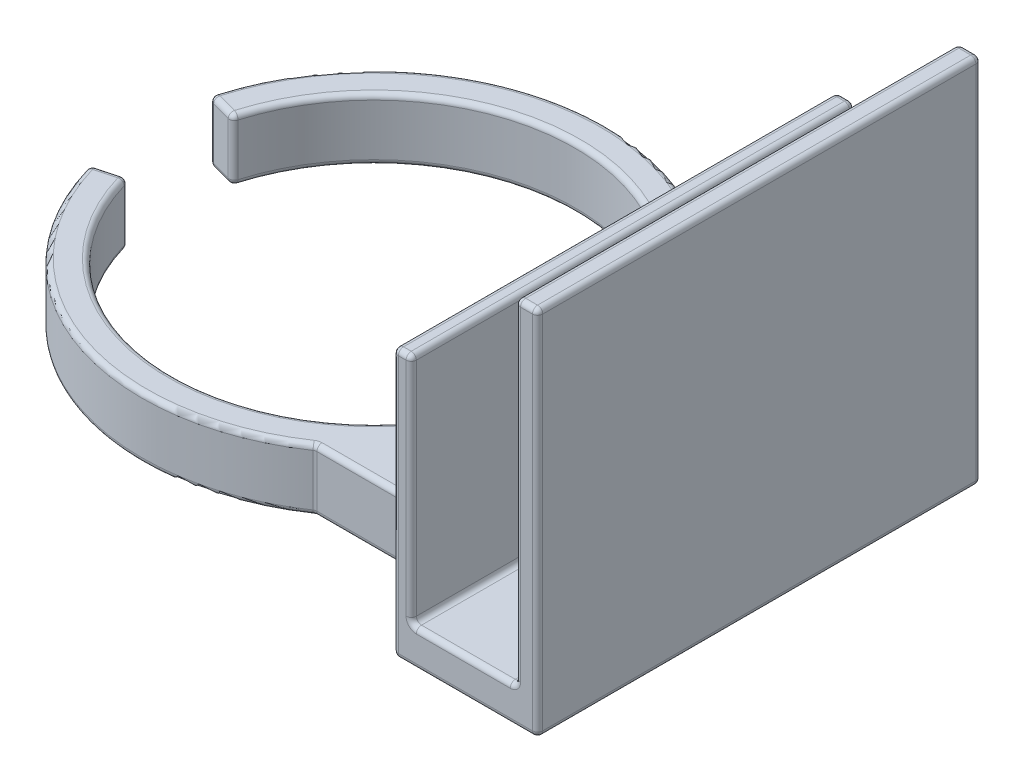
SolidWorks part; units mm, degrees
ref_plane "Front Plane" through (0, 0, 0) normal (0, 0, 1) x (1, 0, 0)
ref_plane "Top Plane" through (0, 0, 0) normal (0, 1, 0) x (1, 0, 0)
ref_plane "Right Plane" through (0, 0, 0) normal (1, 0, 0) x (0, 0, -1)
sketch "Sketch1" plane through (0, 0, 0) normal (0, 1, 0) x (1, 0, 0)
  line L1 (46.7214, 25) -> (46.7214, 5)
  line L2 (44.7214, 5) -> (46.7214, 5)
  line L3 (37.4166, 25) -> (46.7214, 25)
  line L5 (-45, 0) -> (74.7214, 0)
  line L6 (74.7214, 43) -> (74.7214, 0)
  line L7 (25.6125, 37) -> (46.7214, 37)
  line L12 (46.7214, 37) -> (46.7214, 43)
  line L13 (46.7214, 43) -> (74.7214, 43)
  arc A1 (37.4166, 25) -> (44.7214, 5) centre (0, 0) cw
  arc A4 (25.6125, 37) -> (-45, 0) centre (0, 0) ccw
  dimension "D1" = 5
  dimension "D7" = 45
  dimension "D5" = 45
  dimension "D2" = 2
  dimension "D3" = 12
  dimension "D4" = 28
  dimension "D6" = 20
  dimension "D8" = 43
extrude "Boss-Extrude1" add sketch "Sketch1" along normal blind 12
sketch "Sketch3" plane through (0, 12, 0) normal (0, 1, 0) x (1, 0, 0)
  line L2 (-43.4667, 11.6469) -> (-37.6711, 10.0939)
  line L3 (-45, 0) -> (39, 0)
  arc A1 (-45, 0) -> (-43.4667, 11.6469) centre (0, 0) cw
  arc A3 (39, 0) -> (-37.6711, 10.0939) centre (0, 0) ccw
  point P1 (0, 0)
  dimension "D1" = 39
  dimension "D2" = 45
extrude "Cut-Extrude2" cut sketch "Sketch3" against normal through all
ref_plane "Plane1" through (0, 0, 0) normal (0, 0, 1) x (1, 0, 0)
sketch "Sketch4" plane through (0, 12, 0) normal (0, 1, 0) x (1, 0, 0)
  line L0 (-55, 0) -> (55, 0) construction
  line L1 (46.7214, 43) -> (74.7214, 43)
  line L2 (46.7214, 43) -> (46.7214, 0)
  line L3 (46.7214, 0) -> (74.7214, 0)
  line L4 (74.7214, 43) -> (74.7214, 0)
  line L5 (74.7214, 0) -> (74.7214, 43) construction
extrude "Boss-Extrude2" add sketch "Sketch4" along normal blind 50
sketch "Sketch5" plane through (0, 0, 0) normal (0, -1, 0) x (1, 0, 0)
  line L0 (55, 0) -> (-55, 0) construction
  line L1 (74.7214, -43) -> (46.7214, -43)
  line L2 (74.7214, -43) -> (74.7214, 0)
  line L3 (74.7214, 0) -> (46.7214, 0)
  line L4 (46.7214, -43) -> (46.7214, 0)
  line L5 (46.7214, -5) -> (46.7214, -25) construction
extrude "Boss-Extrude3" add sketch "Sketch5" along normal blind 10
sketch "Sketch6" plane through (0, 62, 0) normal (0, 1, 0) x (1, 0, 0)
  line L0 (74.7214, 43) -> (46.7214, 43) construction
  line L1 (50.2117, 43) -> (70.4117, 43)
  line L2 (50.2117, 43) -> (50.2117, 0)
  line L3 (50.2117, 0) -> (70.4117, 0)
  line L4 (70.4117, 43) -> (70.4117, 0)
  line L5 (-55, 0) -> (55, 0) construction
  line L9 (46.7214, 43) -> (46.7214, 0) construction
  dimension "D1" = 20.2
  dimension "D3" = 3.4903
extrude "Cut-Extrude3" cut sketch "Sketch6" against normal blind 65
mirror "Mirror1" about plane through (0, 0, 0) normal (0, 0, 1) of "Boss-Extrude1", "Cut-Extrude2", "Boss-Extrude2", "Boss-Extrude3", "Cut-Extrude3"
sketch "Sketch7" plane through (46.7214, 0, 0) normal (-1, 0, 0) x (0, 0, 1)
  line L0 (43, 62) -> (43, -10) construction
  line L1 (-43, 62) -> (43, 62)
  line L2 (-43, 62) -> (-43, 42)
  line L3 (-43, 42) -> (43, 42)
  line L4 (43, 62) -> (43, 42)
  dimension "D1" = 20
extrude "Cut-Extrude4" cut sketch "Sketch7" against normal up to next
fillet "Fillet5" radius 1 72 edges at (46.7214, 42, 0) (48.4665, 42, -43) (48.4665, 42, 43) (50.2117, 42, 0) (60.3117, -3, 43) (50.2117, 19.5, 43) (70.4117, 29.5, 43) (46.7214, 0, 31) (60.7214, -10, 43) (46.7214, 12, 31) (72.5665, 62, 43) (-40.5689, 0, 10.8704) (-40.5689, 12, 10.8704) (-37.6711, 6, 10.0939) (42.2689, 0, 15.4383) (42.2689, 12, 15.4383) (42.069, 0, 25) (42.069, 12, 25) (45.7214, 0, 5) (45.7214, 12, 5) (44.7214, 6, 5) (46.7214, 6, 5) (37.4166, 6, 25) (46.7214, 6, 25) (-15.5045, 12, 42.2447) (-15.5045, 0, 42.2447) (36.1669, 0, 37) (36.1669, 12, 37) (74.7214, 26, 43) (46.7214, 16, 43) (46.7214, 6, 37) (25.6125, 6, 37) (70.4117, 62, 0) (70.4117, -3, 0) (50.2117, -3, 0) (60.3117, -3, -43) (70.4117, 29.5, -43) (50.2117, 19.5, -43) (46.7214, 0, 0) (74.7214, -10, 0) (74.7214, 62, 0) (46.7214, -10, 0) (60.7214, -10, -43) (72.5665, 62, -43) (39, 12, 0) (39, 0, 0) (-40.5689, 12, -10.8704) (-40.5689, 0, -10.8704) (-37.6711, 6, -10.0939) (-43.4667, 6, -11.6469) (42.2689, 0, -15.4383) (45.7214, 0, -5) (42.069, 0, -25) (42.2689, 12, -15.4383) (45.7214, 12, -5) (42.069, 12, -25) (37.4166, 6, -25) (46.7214, 6, -25) (46.7214, 6, -5) (44.7214, 6, -5) (-15.5045, 0, -42.2447) (36.1669, 0, -37) (-15.5045, 12, -42.2447) (36.1669, 12, -37) (25.6125, 6, -37) (46.7214, 6, -37) (46.7214, 16, -43) (74.7214, 26, -43) (46.7214, 12, 0) (46.7214, 12, -31) (46.7214, 0, -31) (-43.4667, 6, 11.6469)
